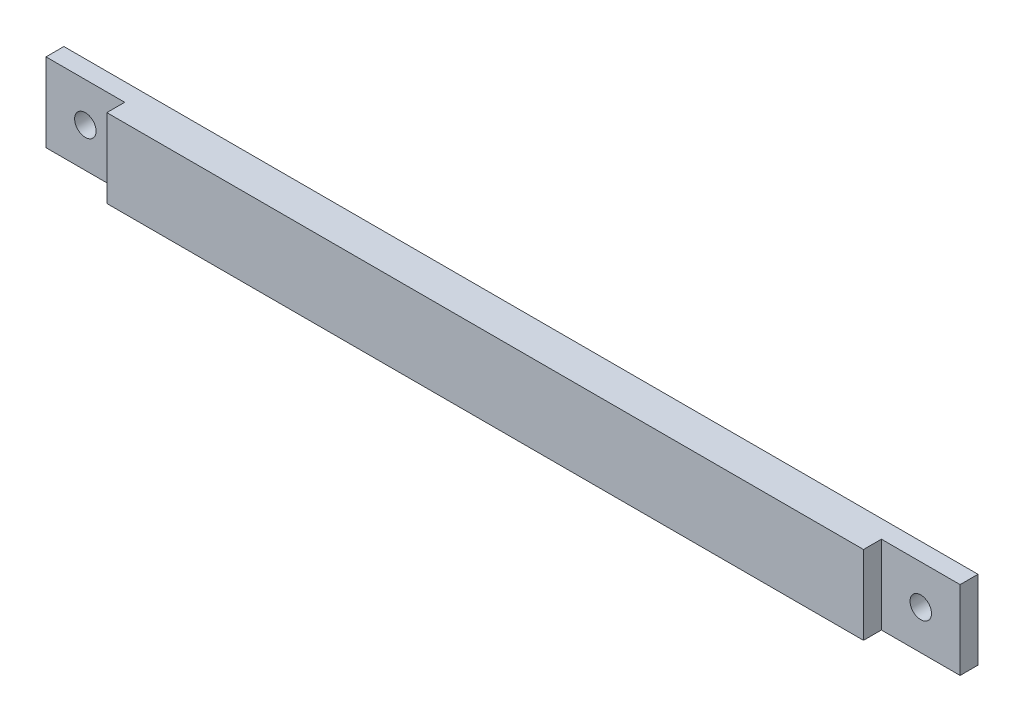
SolidWorks part; units mm, degrees
ref_plane "Plan de face" through (0, 0, 0) normal (0, 0, 1) x (1, 0, 0)
ref_plane "Plan de dessus" through (0, 0, 0) normal (0, 1, 0) x (1, 0, 0)
ref_plane "Plan de droite" through (0, 0, 0) normal (1, 0, 0) x (0, 0, -1)
sketch "Esquisse1" plane through (0, 0, 0) normal (0, 0, 1) x (1, 0, 0)
  line L1 (-138.722, 53.8889) -> (116.768, 53.8889)
  line L2 (-138.722, 53.8889) -> (-138.722, 31.8889)
  line L3 (-138.722, 31.8889) -> (116.768, 31.8889)
  line L4 (116.768, 53.8889) -> (116.768, 31.8889)
  circle A0 centre (-127.722, 42.8889) radius 3
  circle A1 centre (105.768, 42.8889) radius 3
  dimension "D3" = 6
  dimension "D4" = 11
  dimension "D5" = 11
  dimension "D6" = 6
  dimension "D7" = 11
  dimension "D8" = 11
  dimension "D1" = 255.49
  dimension "D2" = 22
extrude "Boss.-Extru.1" add sketch "Esquisse1" along normal blind 10
sketch "Esquisse2" plane through (0, 0, 10) normal (0, 0, 1) x (1, 0, 0)
  line L0 (-138.722, 31.8889) -> (116.768, 31.8889) construction
  line L1 (-138.722, 53.8889) -> (-116.722, 53.8889)
  line L2 (-138.722, 53.8889) -> (-138.722, 31.8889)
  line L3 (-138.722, 31.8889) -> (-116.722, 31.8889)
  line L4 (-116.722, 53.8889) -> (-116.722, 31.8889)
  line L6 (116.768, 53.8889) -> (94.768, 53.8889)
  line L7 (116.768, 53.8889) -> (116.768, 31.8889)
  line L8 (116.768, 31.8889) -> (94.768, 31.8889)
  line L9 (94.768, 53.8889) -> (94.768, 31.8889)
  dimension "D1" = 22
  dimension "D2" = 22
extrude "Enlèv. mat.-Extru.1" cut sketch "Esquisse2" against normal blind 5
